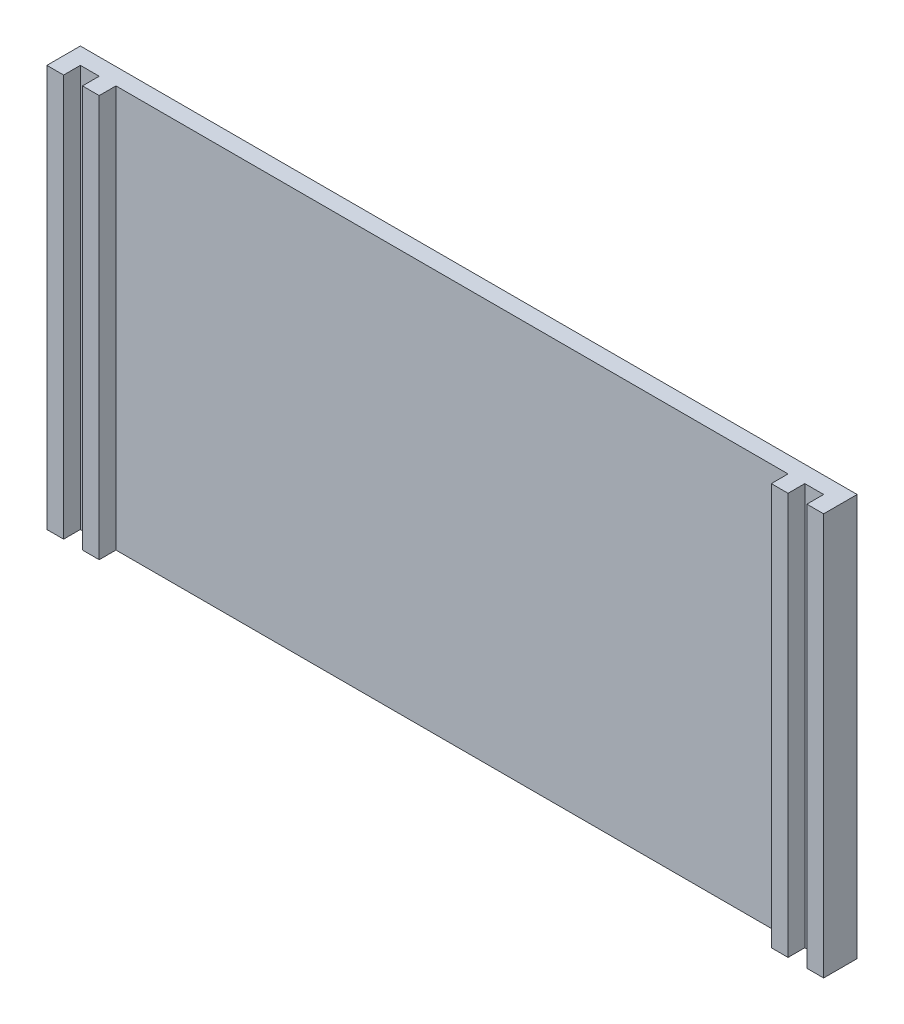
SolidWorks part; units mm, degrees
ref_plane "Front Plane" through (0, 0, 0) normal (0, 0, 1) x (1, 0, 0)
ref_plane "Top Plane" through (0, 0, 0) normal (0, 1, 0) x (1, 0, 0)
ref_plane "Right Plane" through (0, 0, 0) normal (1, 0, 0) x (0, 0, -1)
sketch "Sketch1" plane through (0, 0, 0) normal (0, 1, 0) x (1, 0, 0)
  line L0 (-63.4089, 20.488) -> (122.0911, 20.488)
  line L1 (122.0911, 20.488) -> (122.0911, 12.488)
  line L2 (122.0911, 12.488) -> (118.0911, 12.488)
  line L3 (118.0911, 12.488) -> (118.0911, 16.488)
  line L4 (118.0911, 16.488) -> (113.5911, 16.488)
  line L5 (113.5911, 16.488) -> (113.5911, 12.488)
  line L6 (113.5911, 12.488) -> (109.5911, 12.488)
  line L7 (109.5911, 12.488) -> (109.5911, 16.488)
  line L8 (-63.4089, 20.488) -> (-63.4089, 12.488)
  line L9 (-63.4089, 12.488) -> (-59.4089, 12.488)
  line L10 (-59.4089, 12.488) -> (-59.4089, 16.488)
  line L11 (-59.4089, 16.488) -> (-54.9089, 16.488)
  line L12 (-54.9089, 16.488) -> (-54.9089, 12.488)
  line L13 (-54.9089, 12.488) -> (-50.9089, 12.488)
  line L14 (-50.9089, 12.488) -> (-50.9089, 16.488)
  line L15 (-50.9089, 16.488) -> (109.5911, 16.488)
extrude "Boss-Extrude1" add sketch "Sketch1" along normal blind 96
